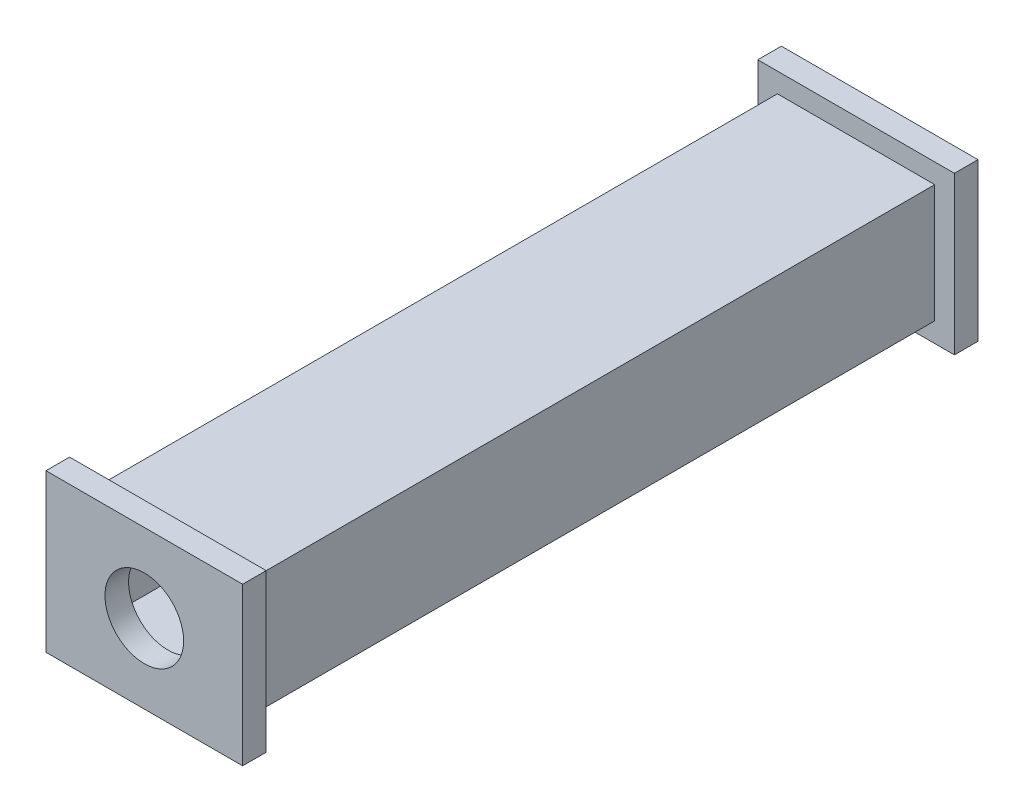
SolidWorks part; units mm, degrees
ref_plane "前视基准面" through (0, 0, 0) normal (0, 0, 1) x (1, 0, 0)
ref_plane "上视基准面" through (0, 0, 0) normal (0, 1, 0) x (1, 0, 0)
ref_plane "右视基准面" through (0, 0, 0) normal (1, 0, 0) x (0, 0, -1)
other "Configuration Table"
sketch "草图8" plane through (0, 0, 0) normal (0, 0, 1) x (1, 0, 0)
  line L1 (-40, 30) -> (40, 30)
  line L2 (-40, 30) -> (-40, -30)
  line L3 (-40, -30) -> (40, -30)
  line L4 (40, 30) -> (40, -30)
  line L5 (-34, 24) -> (34, 24)
  line L6 (-34, 24) -> (-34, -24)
  line L7 (-34, -24) -> (34, -24)
  line L8 (34, 24) -> (34, -24)
extrude "凸台-拉伸1" add sketch "草图8" along normal mid plane 350
sketch "草图9" plane through (0, 0, 175) normal (0, 0, 1) x (1, 0, 0)
  line L1 (-50, 40) -> (50, 40)
  line L2 (-50, 40) -> (-50, -40)
  line L3 (-50, -40) -> (50, -40)
  line L4 (50, 40) -> (50, -40)
  circle A0 centre (0, 0) radius 20
extrude "凸台-拉伸2" add sketch "草图9" along normal blind 12
sketch "草图10" plane through (0, 0, -175) normal (0, 0, -1) x (-1, 0, 0)
  line L1 (-50, 40) -> (50, 40)
  line L2 (-50, 40) -> (-50, -40)
  line L3 (-50, -40) -> (50, -40)
  line L4 (50, 40) -> (50, -40)
  circle A0 centre (0, 0) radius 20
extrude "凸台-拉伸3" add sketch "草图10" along normal blind 12
